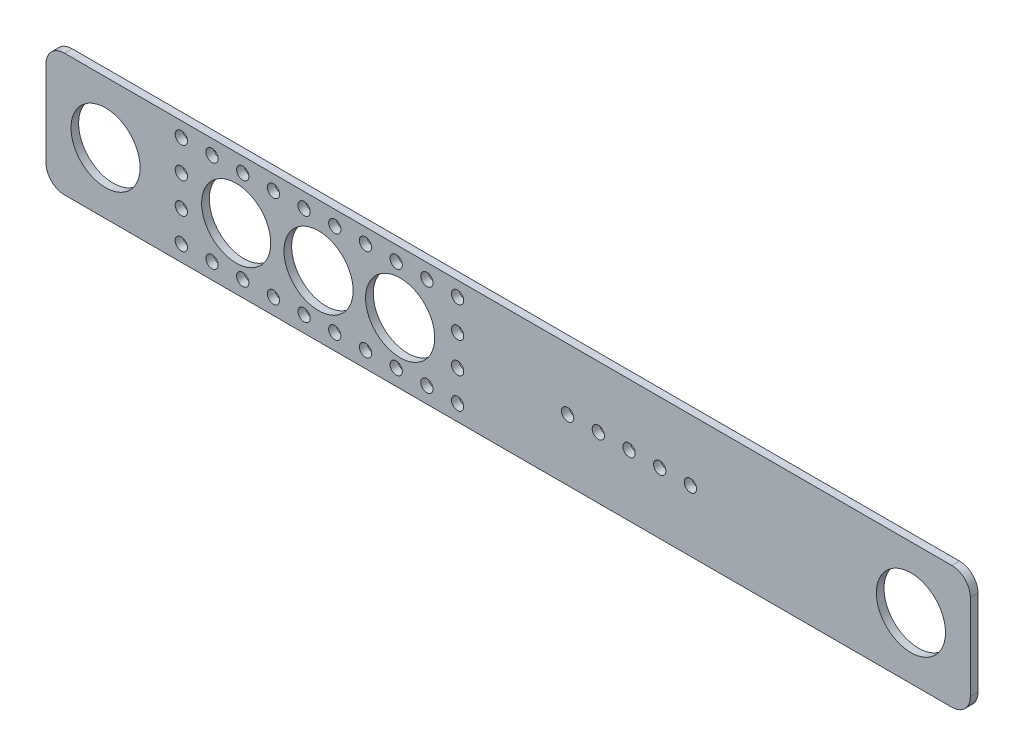
SolidWorks part; units mm, degrees
ref_plane "Front Plane" through (0, 0, 0) normal (0, 0, 1) x (1, 0, 0)
ref_plane "Top Plane" through (0, 0, 0) normal (0, 1, 0) x (1, 0, 0)
ref_plane "Right Plane" through (0, 0, 0) normal (1, 0, 0) x (0, 0, -1)
sketch "Sketch1" plane through (0, 0, 0) normal (0, 0, 1) x (1, 0, 0)
  line L1 (-58.961, 34.7527) -> (323.4919, 34.7527)
  line L2 (-58.961, 34.7527) -> (-58.961, -16.0473)
  line L3 (-58.961, -16.0473) -> (323.4919, -16.0473)
  line L4 (323.4919, 34.7527) -> (323.4919, -16.0473)
  circle A0 centre (-34.3348, 9.3527) radius 14.3002
  circle A1 centre (298.9132, 9.3527) radius 14.3002
  circle A2 centre (53.8032, 9.3527) radius 14.3002
  circle A3 centre (87.5734, 9.3527) radius 14.3002
  circle A4 centre (19.7296, 9.3527) radius 14.3002
  circle A39 centre (156.8772, 9.3527) radius 2.54
  circle A40 centre (169.5772, 9.3527) radius 2.54
  circle A41 centre (182.2772, 9.3527) radius 2.54
  circle A42 centre (194.9772, 9.3527) radius 2.54
  circle A43 centre (207.6772, 9.3527) radius 2.54
  circle A85 centre (-2.9686, 28.6693) radius 2.54 construction
  circle A86 centre (-2.9686, 28.6693) radius 2.54
  circle A87 centre (9.7314, 28.6693) radius 2.54
  circle A88 centre (22.4314, 28.6693) radius 2.54
  circle A89 centre (35.1314, 28.6693) radius 2.54
  circle A90 centre (47.8314, 28.6693) radius 2.54
  circle A91 centre (60.5314, 28.6693) radius 2.54
  circle A92 centre (73.2314, 28.6693) radius 2.54
  circle A93 centre (85.9314, 28.6693) radius 2.54
  circle A94 centre (98.6314, 28.6693) radius 2.54
  circle A96 centre (111.3314, 28.6693) radius 2.54
  circle A105 centre (111.3314, 15.9693) radius 2.54
  circle A114 centre (111.3314, 3.2693) radius 2.54
  circle A115 centre (9.7314, -9.4307) radius 2.54
  circle A116 centre (22.4314, -9.4307) radius 2.54
  circle A117 centre (35.1314, -9.4307) radius 2.54
  circle A118 centre (47.8314, -9.4307) radius 2.54
  circle A119 centre (60.5314, -9.4307) radius 2.54
  circle A120 centre (73.2314, -9.4307) radius 2.54
  circle A121 centre (85.9314, -9.4307) radius 2.54
  circle A122 centre (98.6314, -9.4307) radius 2.54
  circle A123 centre (111.3314, -9.4307) radius 2.54
  circle A124 centre (-2.9686, 15.9693) radius 2.54
  circle A125 centre (-2.9686, 3.2693) radius 2.54
  circle A126 centre (-2.9686, -9.4307) radius 2.54
  circle A127 centre (98.6314, 15.9693) radius 2.54 [skipped]
  circle A128 centre (98.6314, 3.2693) radius 2.54 [skipped]
  circle A129 centre (85.9314, 3.2693) radius 2.54 [skipped]
  circle A130 centre (85.9314, 15.9693) radius 2.54 [skipped]
  circle A131 centre (73.2314, 15.9693) radius 2.54 [skipped]
  circle A132 centre (73.2314, 3.2693) radius 2.54 [skipped]
  circle A133 centre (60.5314, 15.9693) radius 2.54 [skipped]
  circle A134 centre (60.5314, 3.2693) radius 2.54 [skipped]
  circle A135 centre (47.8314, 3.2693) radius 2.54 [skipped]
  circle A136 centre (47.8314, 15.9693) radius 2.54 [skipped]
  circle A137 centre (35.1314, 15.9693) radius 2.54 [skipped]
  circle A138 centre (35.1314, 3.2693) radius 2.54 [skipped]
  circle A139 centre (22.4314, 3.2693) radius 2.54 [skipped]
  circle A140 centre (22.4314, 15.9693) radius 2.54 [skipped]
  circle A141 centre (9.7314, 15.9693) radius 2.54 [skipped]
  circle A142 centre (9.7314, 3.2693) radius 2.54 [skipped]
  dimension "D3" = 25.4
  dimension "D4" = 5
  dimension "D7" = 10
  dimension "D1" = 50.8
  dimension "D2" = 25.4
  dimension "D5" = 88.138
  dimension "D6" = 245.11
  dimension "D8" = 4
extrude "Boss-Extrude1" add sketch "Sketch1" along normal blind 3.175
fillet "Fillet1" radius 7.62 4 edges at (323.4919, 34.7527, 1.5875) (323.4919, -16.0473, 1.5875) (-58.961, -16.0473, 1.5875) (-58.961, 34.7527, 1.5875)
